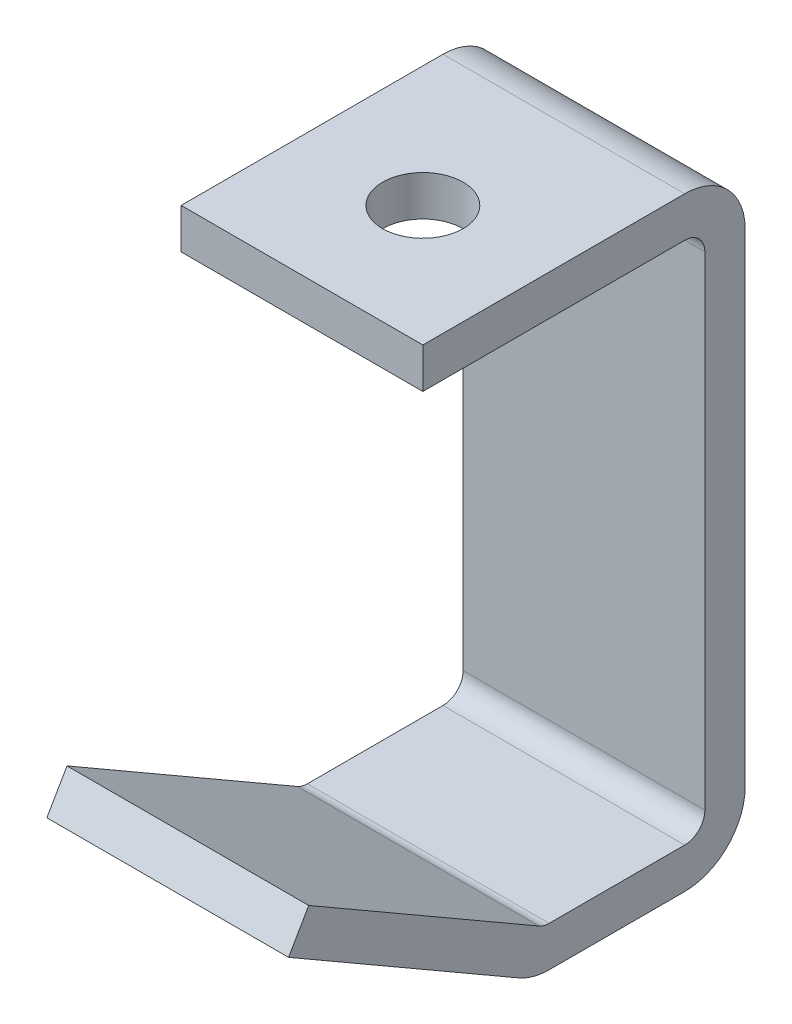
SolidWorks part; units mm, degrees
ref_plane "정면" through (0, 0, 0) normal (0, 0, 1) x (1, 0, 0)
ref_plane "윗면" through (0, 0, 0) normal (0, 1, 0) x (1, 0, 0)
ref_plane "우측면" through (0, 0, 0) normal (1, 0, 0) x (0, 0, -1)
ref_plane "평면1" through (38.1, 0, 0) normal (1, 0, 0) x (0, 0, -1)
sketch "스케치1" plane through (38.1, 0, 0) normal (1, 0, 0) x (0, 0, -1)
  line L0 (0, 0) -> (0, 6.35)
  line L1 (0, 6.35) -> (-31.75, 6.35)
  line L2 (-31.75, 6.35) -> (-68.793, 27.7368)
  line L3 (-68.793, 27.7368) -> (-71.968, 22.2375)
  line L4 (-71.968, 22.2375) -> (-33.4515, 0)
  line L5 (-33.4515, 0) -> (0, 0)
extrude "보스-돌출1" add sketch "스케치1" against normal blind 38.1
sketch "스케치2" plane through (0, 6.35, 0) normal (0, 1, 0) x (-1, 0, 0)
  line L0 (0, 6.35) -> (0, 0)
  line L1 (0, 0) -> (-38.1, 0)
  line L2 (-38.1, 0) -> (-38.1, 6.35)
  line L3 (-38.1, 6.35) -> (0, 6.35)
extrude "보스-돌출2" add sketch "스케치2" along normal blind 88.9
sketch "스케치3" plane through (0, 0, 6.35) normal (0, 0, 1) x (1, 0, 0)
  line L0 (0, 88.9) -> (0, 95.25)
  line L1 (0, 95.25) -> (38.1, 95.25)
  line L2 (38.1, 95.25) -> (38.1, 88.9)
  line L3 (38.1, 88.9) -> (0, 88.9)
extrude "보스-돌출3" add sketch "스케치3" along normal blind 44.45
hole_wizard "구멍1" positions "스케치5" profile "스케치4" legacy
sketch "스케치5" plane through (0, 95.25, 0) normal (0, 1, 0) x (1, 0, 0)
  point P0 (19.05, -31.75)
sketch "스케치4" plane through (19.05, 95.25, 31.75) normal (1, 0, 0) x (0, 0, 1)
  line L0 (0, 0) -> (0, 6.35)
  line L1 (0, 6.35) -> (6.35, 6.35)
  line L2 (6.35, 6.35) -> (6.35, 0)
  line L3 (6.35, 0) -> (0, 0)
  line L4 (0, 110) -> (0, -10) construction
  dimension "지름" = 12.7
  dimension "깊이" = 6.35
fillet "필렛1" radius 3.175 3 edges at (19.05, 6.35, 6.35) (19.05, 6.35, 31.75) (19.05, 88.9, 6.35)
fillet "필렛2" radius 9.525 3 edges at (19.05, 0, 33.4515) (19.05, 95.25, 0) (19.05, 0, 0)
